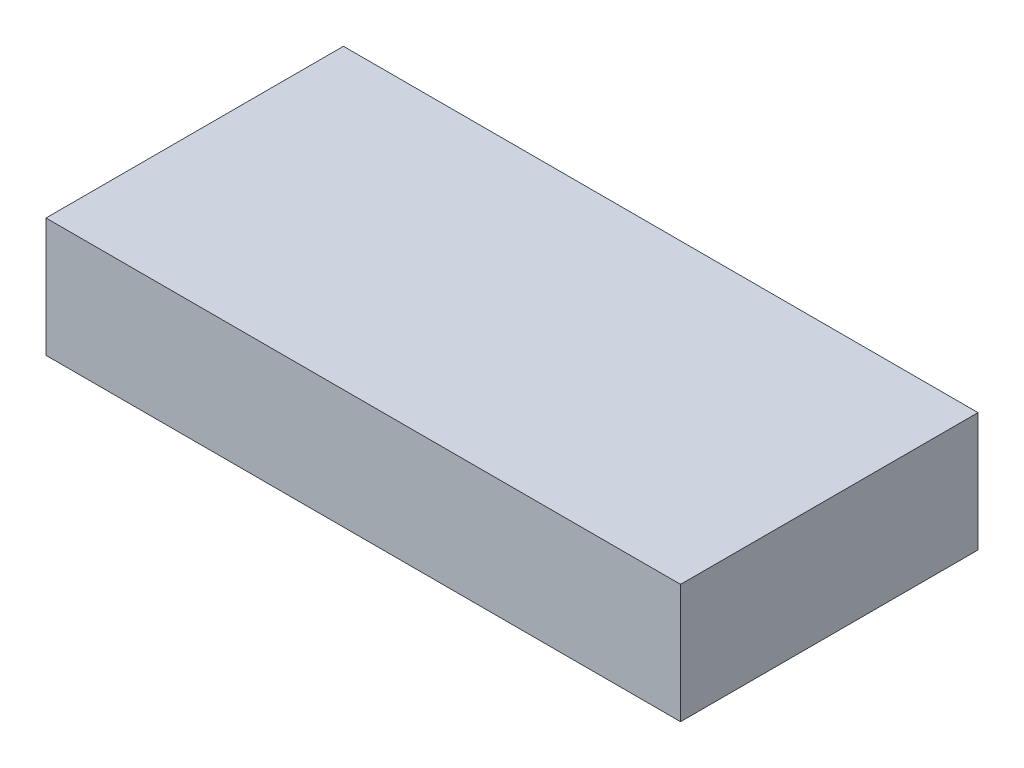
SolidWorks part; units mm, degrees
material "Pine"
ref_plane "Front Plane" through (0, 0, 0) normal (0, 0, 1) x (1, 0, 0)
ref_plane "Top Plane" through (0, 0, 0) normal (0, 1, 0) x (1, 0, 0)
ref_plane "Right Plane" through (0, 0, 0) normal (1, 0, 0) x (0, 0, -1)
sketch "Sketch1" plane through (0, 0, 0) normal (0, 0, 1) x (1, 0, 0)
  line L1 (-50.8, -9.525) -> (50.8, -9.525)
  line L2 (-50.8, -9.525) -> (-50.8, 9.525)
  line L3 (-50.8, 9.525) -> (50.8, 9.525)
  line L4 (50.8, -9.525) -> (50.8, 9.525)
  line L5 (-50.8, -9.525) -> (50.8, 9.525) construction
  line L6 (-50.8, 9.525) -> (50.8, -9.525) construction
  point P0 (0, 0)
  dimension "D1" = 19.05
  dimension "D2" = 101.6
extrude "Boss-Extrude1" add sketch "Sketch1" along normal mid plane 47.625
